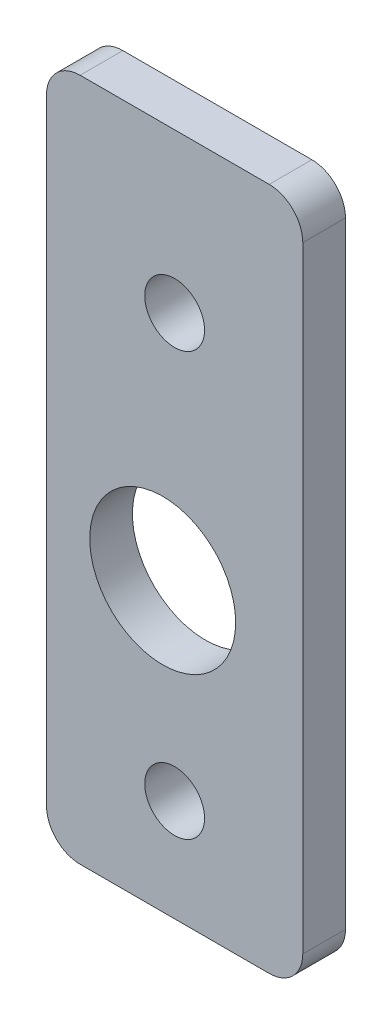
SolidWorks part; units mm, degrees
ref_plane "Front Plane" through (0, 0, 0) normal (0, 0, 1) x (1, 0, 0)
ref_plane "Top Plane" through (0, 0, 0) normal (0, 1, 0) x (1, 0, 0)
ref_plane "Right Plane" through (0, 0, 0) normal (1, 0, 0) x (0, 0, -1)
sketch "Sketch1" plane through (0, 0, 0) normal (0, 0, 1) x (1, 0, 0)
  line L0 (-19.05, -177.8) -> (-19.05, 177.8) construction
  line L1 (-19.05, -177.8) -> (-19.05, 177.8) construction
  line L2 (19.05, -177.8) -> (19.05, 177.8) construction
  line L3 (19.05, -177.8) -> (19.05, 177.8) construction
  line L4 (19.05, -177.8) -> (-19.05, -177.8)
  line L5 (19.05, -76.2) -> (-19.05, -76.2)
  line L6 (19.05, -177.8) -> (19.05, -76.2)
  line L7 (-19.05, -177.8) -> (-19.05, -76.2)
  circle A0 centre (-1.778, -135.128) radius 10.85
  dimension "D1" = 101.6
extrude "Boss-Extrude1" add sketch "Sketch1" along normal blind 6.35
fillet "Fillet1" radius 5 1 edges at (-19.05, -76.2, 3.175)
fillet "Fillet2" radius 5 1 edges at (19.05, -76.2, 3.175)
fillet "Fillet3" radius 5 1 edges at (19.05, -177.8, 3.175)
fillet "Fillet4" radius 5 1 edges at (-19.05, -177.8, 3.175)
sketch "Sketch2" plane through (0, 0, 6.35) normal (0, 0, 1) x (1, 0, 0)
  line L0 (0, -76.2) -> (0, -177.8) construction
  line L1 (14.05, -76.2) -> (-14.05, -76.2) construction
  line L2 (-14.05, -177.8) -> (14.05, -177.8) construction
  circle A0 centre (0, -99.7884) radius 4.445
  circle A1 centre (0, -162.6255) radius 4.445
  dimension "D1" = 8.89
extrude "Cut-Extrude1" cut sketch "Sketch2" against normal up to next
